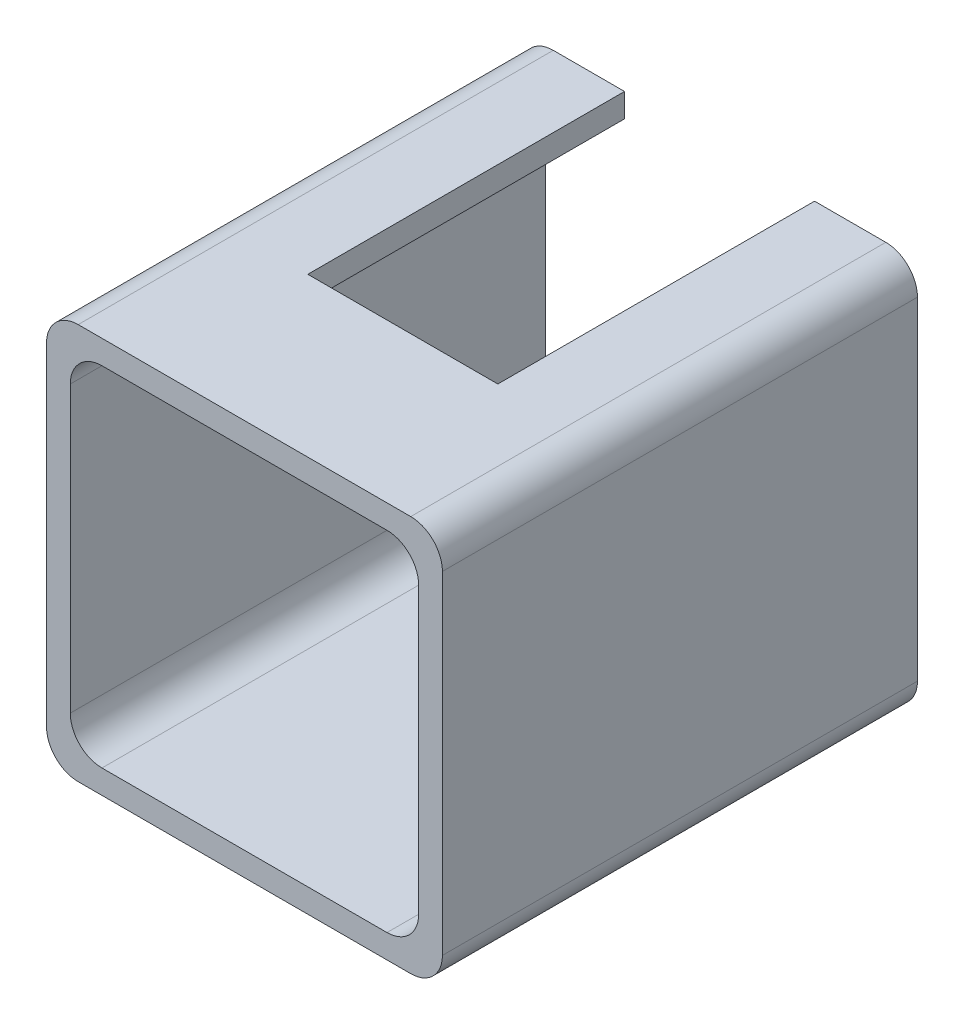
SolidWorks part; units mm, degrees
ref_plane "前视基准面" through (0, 0, 0) normal (0, 0, 1) x (1, 0, 0)
ref_plane "上视基准面" through (0, 0, 0) normal (0, 1, 0) x (1, 0, 0)
ref_plane "右视基准面" through (0, 0, 0) normal (1, 0, 0) x (0, 0, -1)
sketch "草图1" plane through (0, 0, 0) normal (0, 0, 1) x (1, 0, 0)
  line L0 (12.5, 10.5) -> (12.5, -10.5)
  line L1 (-9, 11) -> (9, 11)
  line L2 (-11, 9) -> (-11, -9)
  line L3 (-9, -11) -> (9, -11)
  line L4 (11, 9) -> (11, -9)
  line L5 (-11, 11) -> (11, -11) construction
  line L6 (-11, -11) -> (11, 11) construction
  line L7 (-10.5, -12.5) -> (10.5, -12.5)
  line L8 (-12.5, 10.5) -> (-12.5, -10.5)
  line L9 (-10.5, 12.5) -> (10.5, 12.5)
  line L10 (-12.5, -12.5) -> (12.5, -12.5) construction
  line L11 (-12.5, 12.5) -> (-12.5, -12.5) construction
  line L12 (12.5, 12.5) -> (12.5, -12.5) construction
  line L13 (-12.5, 12.5) -> (12.5, 12.5) construction
  line L14 (-11, 11) -> (-11, -11) construction
  line L15 (-11, -11) -> (11, -11) construction
  line L16 (11, 11) -> (11, -11) construction
  line L17 (-11, 11) -> (11, 11) construction
  arc A0 (-10.5, -12.5) -> (-12.5, -10.5) centre (-10.5, -10.5) cw
  arc A1 (12.5, -10.5) -> (10.5, -12.5) centre (10.5, -10.5) cw
  arc A2 (12.5, 10.5) -> (10.5, 12.5) centre (10.5, 10.5) ccw
  arc A3 (-12.5, 10.5) -> (-10.5, 12.5) centre (-10.5, 10.5) cw
  arc A4 (-11, -9) -> (-9, -11) centre (-9, -9) ccw
  arc A5 (9, -11) -> (11, -9) centre (9, -9) ccw
  arc A6 (9, 11) -> (11, 9) centre (9, 9) cw
  arc A7 (-9, 11) -> (-11, 9) centre (-9, 9) ccw
  point P0 (0, 0)
  dimension "D4" = 2
  dimension "D1" = 22
  dimension "D2" = 22
  dimension "D3" = 1.5
extrude "凸台-拉伸1" add sketch "草图1" along normal blind 30
sketch "草图2" plane through (0, 12.5, 0) normal (0, 1, 0) x (1, 0, 0)
  line L0 (10.5, 0) -> (-10.5, 0) construction
  line L1 (-6, 0) -> (6, 0)
  line L2 (-6, 0) -> (-6, -20)
  line L3 (-6, -20) -> (6, -20)
  line L4 (6, 0) -> (6, -20)
  point P6 (0, 0)
  dimension "D1" = 12
  dimension "D2" = 20
extrude "切除-拉伸1" cut sketch "草图2" against normal up to next
